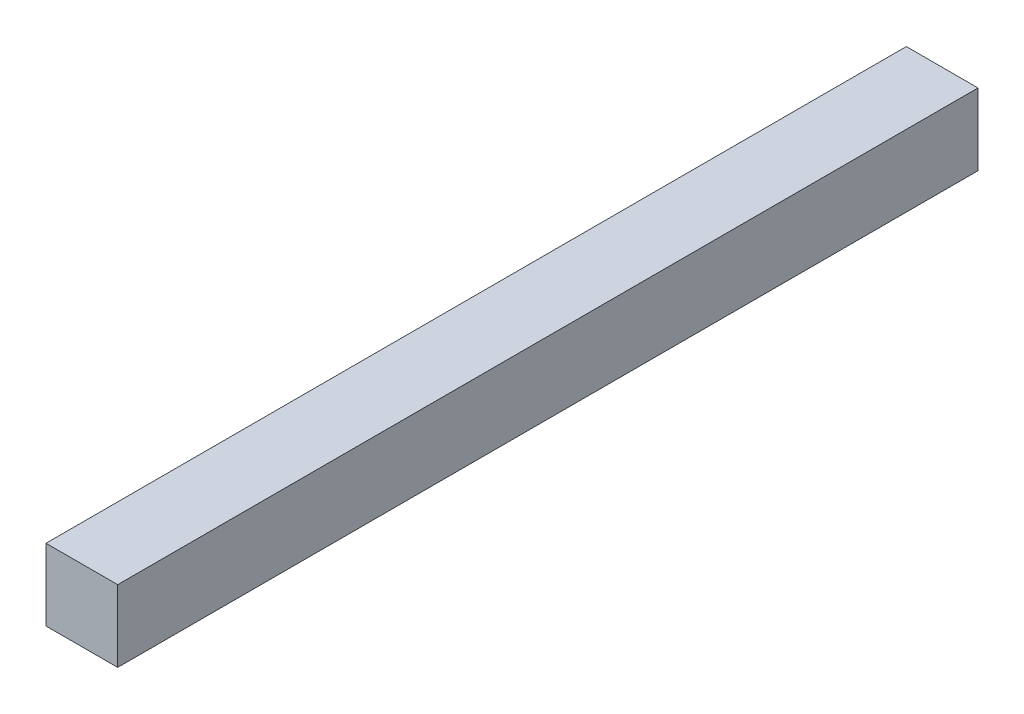
SolidWorks part; units mm, degrees
ref_plane "Front Plane" through (0, 0, 0) normal (0, 0, 1) x (1, 0, 0)
ref_plane "Top Plane" through (0, 0, 0) normal (0, 1, 0) x (1, 0, 0)
ref_plane "Right Plane" through (0, 0, 0) normal (1, 0, 0) x (0, 0, -1)
sketch "Sketch1" plane through (0, 0, 0) normal (1, 0, 0) x (0, 0, -1)
  line L0 (126.5431, 0) -> (-135.6999, 0) construction
  line L1 (0, 105.7009) -> (0, -97.8505) construction
  line L3 (-120, 10) -> (120, 10)
  line L4 (-120, 10) -> (-120, -10)
  line L5 (-120, -10) -> (120, -10)
  line L6 (120, 10) -> (120, -10)
  point P9 (120, 0)
  point P10 (0, 10)
  dimension "D1" = 20
  dimension "D2" = 240
extrude "Boss-Extrude1" add sketch "Sketch1" along normal blind 20
sketch "Sketch2" plane through (0, 0, 0) normal (1, 0, 0) x (0, 0, -1)
  line L0 (-120, 0) -> (120, 0) construction
  line L1 (0, 22.843) -> (0, -26.6092) construction
  line L2 (-120, 10) -> (-120, -10) construction
  line L3 (-120, 10) -> (-120, -10) construction
  line L4 (120, -10) -> (120, 10) construction
  line L5 (120, -10) -> (120, 10) construction
  text T0 "length" font "Century Gothic" height in points 20
  point P10 (0, 0)
extrude "Cut-Extrude1" cut sketch "Sketch2" along normal blind 4
